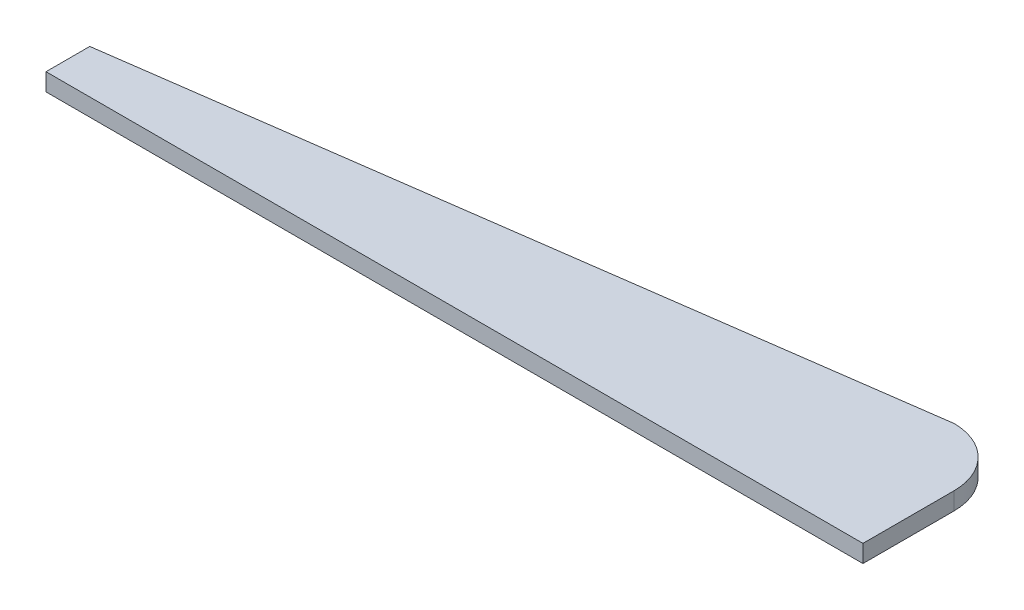
SolidWorks part; units mm, degrees
ref_plane "Front Plane" through (0, 0, 0) normal (0, 0, 1) x (1, 0, 0)
ref_plane "Top Plane" through (0, 0, 0) normal (0, 1, 0) x (1, 0, 0)
ref_plane "Right Plane" through (0, 0, 0) normal (1, 0, 0) x (0, 0, -1)
sketch "Sketch1" plane through (0, 0, 0) normal (0, 1, 0) x (1, 0, 0)
  line L0 (39.0375, -3.3567) -> (39.0375, 27.8433)
  line L1 (39.0375, -3.3567) -> (-240.9625, -3.3567)
  line L2 (-240.9625, -3.3567) -> (-240.9625, 11.6433)
  line L3 (-240.9625, 11.6433) -> (19.0375, 47.8433)
  arc A0 (19.0375, 47.8433) -> (39.0375, 27.8433) centre (19.0375, 27.8433) cw
extrude "Boss-Extrude1" add sketch "Sketch1" along normal blind 6
